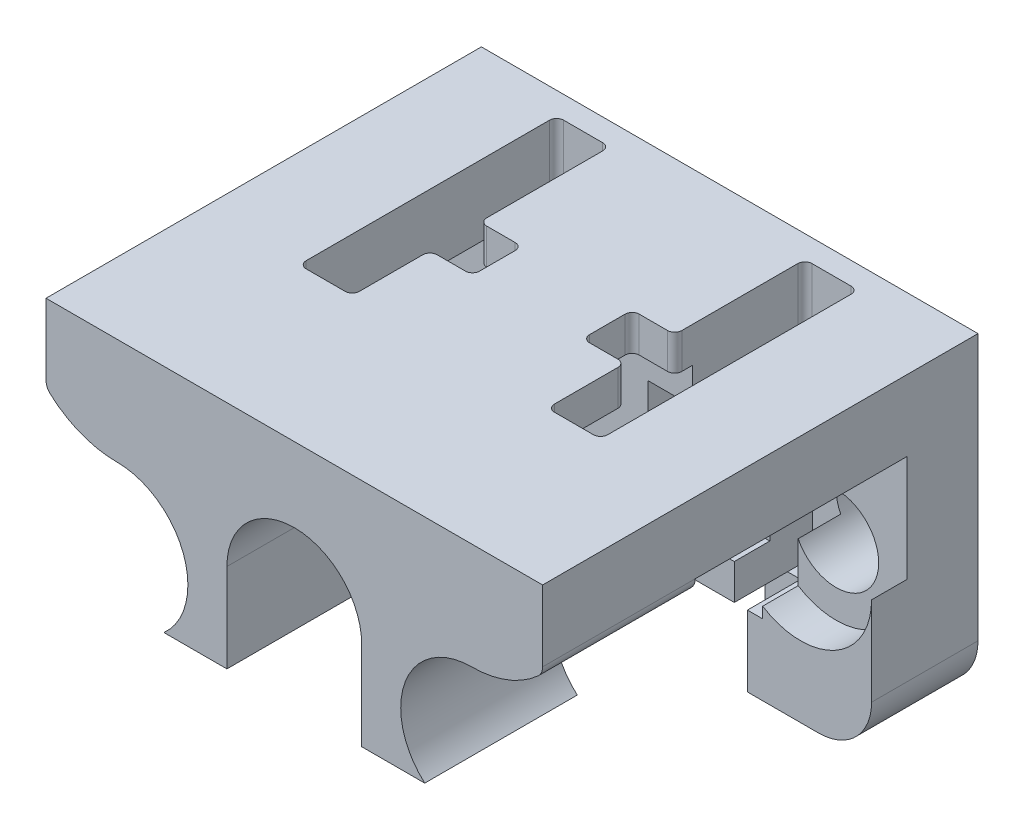
SolidWorks part; units mm, degrees
ref_plane "Front Plane" through (0, 0, 0) normal (0, 0, 1) x (1, 0, 0)
ref_plane "Top Plane" through (0, 0, 0) normal (0, 1, 0) x (1, 0, 0)
ref_plane "Right Plane" through (0, 0, 0) normal (1, 0, 0) x (0, 0, -1)
sketch "Sketch1" plane through (0, 0, 0) normal (0, 0, 1) x (1, 0, 0)
  line L1 (-7, -3.5) -> (7, -3.5)
  line L2 (-7, -3.5) -> (-7, 3.5)
  line L3 (-7, 3.5) -> (7, 3.5)
  line L4 (7, -3.5) -> (7, 3.5)
  line L5 (-7, -3.5) -> (7, 3.5) construction
  line L6 (-7, 3.5) -> (7, -3.5) construction
  point P0 (0, 0)
  dimension "D1" = 14
  dimension "D2" = 7
extrude "Boss-Extrude1" add sketch "Sketch1" along normal blind 2
fillet "Fillet1" radius 1.5 2 edges at (-7, -3.5, 1) (7, -3.5, 1)
hole_wizard "M2 Clearance Hole1" positions "Sketch2" profile "Sketch3" hole size "M2" standard "ISO" end condition through all
sketch "Sketch2" plane through (0, 0, 2) normal (0, 0, 1) x (1, 0, 0)
  line L0 (7, 3.5) -> (-7, 3.5) construction
  line L1 (0, 0) -> (0, 2.7622) construction
  point P0 (-5, 0.5)
  point P2 (5, 0.5)
  dimension "D1" = 3
  dimension "D2" = 10
sketch "Sketch3" plane through (-5, 0.5, 2) normal (1, 0, 0) x (0, -1, 0)
  line L0 (0, 0) -> (0, 2)
  line L1 (0, 2) -> (1.2, 2)
  line L2 (1.2, 2) -> (1.2, 0)
  line L5 (1.2, 0) -> (0, 0)
  line L11 (0, -6.35) -> (0, 107.95) construction
  dimension "Thru Hole Dia." = 2.4
  dimension "Thru Hole Depth" = 2
sketch "Sketch4" plane through (0, 3.5, 0) normal (0, 1, 0) x (1, 0, 0)
  line L0 (7, 0) -> (-7, 0) construction
  line L1 (-7, 0) -> (7, 0)
  line L2 (-7, 0) -> (-7, -12.2738)
  line L3 (-7, -12.2738) -> (7, -12.2738)
  line L4 (7, 0) -> (7, -12.2738)
extrude "Boss-Extrude2" add sketch "Sketch4" along normal blind 2
sketch "Sketch5" plane through (0, 0, 2) normal (0, 0, 1) x (1, 0, 0)
  line L0 (-5.5, -3.5) -> (5.5, -3.5) construction
  line L1 (-5.5, -3.5) -> (5.5, -3.5)
  line L2 (7, -2) -> (7, 3.5) construction
  line L3 (-7, 3.5) -> (-7, -2) construction
  line L4 (7, -2) -> (7, 3.5)
  line L5 (-7, 3.5) -> (-7, -2)
  line L6 (-3.2679, -0.5) -> (3.2679, -0.5)
  arc A0 (5.5, -3.5) -> (7, -2) centre (5.5, -2) ccw construction
  arc A1 (-7, -2) -> (-5.5, -3.5) centre (-5.5, -2) ccw construction
  arc A2 (5.5, -3.5) -> (7, -2) centre (5.5, -2) ccw
  arc A3 (-7, -2) -> (-5.5, -3.5) centre (-5.5, -2) ccw
  circle A4 centre (-5, 0.5) radius 2
  circle A5 centre (5, 0.5) radius 2
  arc M7 (-7, -2) -> (-5.5, -3.5) centre (-5.5, -2) ccw
  line M8 (-5.5, -3.5) -> (5.5, -3.5)
  arc M9 (5.5, -3.5) -> (7, -2) centre (5.5, -2) ccw
  line M10 (7, -2) -> (7, 3.5)
  dimension "D1" = 3
extrude "Boss-Extrude3" add sketch "Sketch5" along normal blind 1 contours A5 L6 A4 L5 M7 M8 M9 M10
sketch "Sketch6" plane through (0, 0, 0) normal (0, 0, -1) x (-1, 0, 0)
  line L0 (5.5, -3.5) -> (-5.5, -3.5) construction
  line L1 (-2.5, -3.5) -> (2.5, -3.5)
  line L2 (-2.5, -3.5) -> (-2.5, 0)
  line L3 (-2.5, 0) -> (2.5, 0)
  line L4 (2.5, -3.5) -> (2.5, 0)
  line L5 (5.5, -3.5) -> (-5.5, -3.5) construction
  point P11 (0, -3.5)
  dimension "D1" = 5
  dimension "D2" = 3.5
extrude "Cut-Extrude1" cut sketch "Sketch6" against normal blind 1.5
sketch "Sketch7" plane through (0, 0, 1.5) normal (0, 0, -1) x (-1, 0, 0)
  line L1 (-3.5, -3.5) -> (3.5, -3.5)
  line L2 (-3.5, -3.5) -> (-3.5, -1.5)
  line L3 (-3.5, -1.5) -> (3.5, -1.5)
  line L4 (3.5, -3.5) -> (3.5, -1.5)
  line L5 (-2.5, -3.5) -> (-5.5, -3.5) construction
  point P5 (0, -3.5)
  dimension "D1" = 2
  dimension "D2" = 7
extrude "Cut-Extrude2" cut sketch "Sketch7" against normal up to next
sketch "Sketch8" plane through (0, 0, 2) normal (0, 0, 1) x (1, 0, 0)
  line L1 (-1.5, -1.5) -> (1.5, -1.5)
  line L2 (-1.5, -1.5) -> (-1.5, 3.5)
  line L3 (-1.5, 3.5) -> (1.5, 3.5)
  line L4 (1.5, -1.5) -> (1.5, 3.5)
  line L5 (7, 3.5) -> (-7, 3.5) construction
  line L6 (-3.5, -1.5) -> (3.5, -1.5) construction
  circle A0 centre (-5, 0.5) radius 2
  circle A1 centre (5, 0.5) radius 2
  arc A2 (3.2679, -0.5) -> (7, 0.5) centre (5, 0.5) ccw construction
  point P17 (0, -1.5)
  line M8 (-3.2679, -0.5) -> (3.2679, -0.5)
  line M12 (7, 3.5) -> (-7, 3.5)
  dimension "D1" = 3
extrude "Boss-Extrude4" add sketch "Sketch8" along normal blind 1.8 contours L4 L2 M8 M12 | L1 L4 L2 M8
sketch "Sketch9" plane through (0, 5.5, 0) normal (0, 1, 0) x (1, 0, 0)
  line L0 (7, 0) -> (-7, 0) construction
  line L1 (-2.95, -7.89) -> (-4.05, -7.89)
  line L2 (-2.75, -7.69) -> (-2.75, -5.9)
  line L3 (-2.95, -0.63) -> (-4.05, -0.63)
  line L4 (-4.25, -7.69) -> (-4.25, -0.83)
  line L5 (-7, 0) -> (-7, -12.2738) construction
  line L6 (0, 0) -> (0, -11.1853) construction
  line L11 (-2.55, -5.7) -> (-1.75, -5.7)
  line L12 (-1.55, -5.5) -> (-1.55, -4.5)
  line L13 (-1.75, -4.3) -> (-2.55, -4.3)
  line L14 (-2.75, -4.1) -> (-2.75, -0.83)
  line L15 (2.75, -4.1) -> (2.75, -0.83)
  line L16 (1.75, -4.3) -> (2.55, -4.3)
  line L17 (1.55, -5.5) -> (1.55, -4.5)
  line L18 (2.55, -5.7) -> (1.75, -5.7)
  line L19 (4.25, -7.69) -> (4.25, -0.83)
  line L20 (2.95, -0.63) -> (4.05, -0.63)
  line L21 (2.75, -7.69) -> (2.75, -5.9)
  line L22 (2.95, -7.89) -> (4.05, -7.89)
  arc A0 (-2.95, -7.89) -> (-2.75, -7.69) centre (-2.95, -7.69) ccw
  arc A1 (-2.75, -0.83) -> (-2.95, -0.63) centre (-2.95, -0.83) ccw
  arc A2 (-4.05, -0.63) -> (-4.25, -0.83) centre (-4.05, -0.83) ccw
  arc A3 (-4.05, -7.89) -> (-4.25, -7.69) centre (-4.05, -7.69) cw
  arc A8 (-2.55, -5.7) -> (-2.75, -5.9) centre (-2.55, -5.9) ccw
  arc A9 (-1.75, -5.7) -> (-1.55, -5.5) centre (-1.75, -5.5) ccw
  arc A10 (-1.55, -4.5) -> (-1.75, -4.3) centre (-1.75, -4.5) ccw
  arc A11 (-2.55, -4.3) -> (-2.75, -4.1) centre (-2.55, -4.1) cw
  arc A12 (2.55, -4.3) -> (2.75, -4.1) centre (2.55, -4.1) ccw
  arc A13 (1.55, -4.5) -> (1.75, -4.3) centre (1.75, -4.5) cw
  arc A14 (1.75, -5.7) -> (1.55, -5.5) centre (1.75, -5.5) cw
  arc A15 (2.55, -5.7) -> (2.75, -5.9) centre (2.55, -5.9) cw
  arc A16 (4.05, -7.89) -> (4.25, -7.69) centre (4.05, -7.69) ccw
  arc A17 (4.05, -0.63) -> (4.25, -0.83) centre (4.05, -0.83) cw
  arc A18 (2.75, -0.83) -> (2.95, -0.63) centre (2.95, -0.83) cw
  arc A19 (2.95, -7.89) -> (2.75, -7.69) centre (2.95, -7.69) cw
  point P12 (-2.75, -7.89)
  point P15 (-2.75, -0.63)
  point P18 (-4.25, -0.63)
  point P51 (-2.75, -4.3)
  point P61 (2.75, -4.3)
  point P62 (4.25, -0.63)
  point P63 (2.75, -0.63)
  point P64 (2.75, -7.89)
  dimension "D5" = 0.2
  dimension "D9" = 0.2
  dimension "D1" = 1.5
  dimension "D2" = 7.26
  dimension "D3" = 0.63
  dimension "D4" = 2.75
  dimension "D6" = 1.2
  dimension "D7" = 1.4
  dimension "D8" = 4.3
extrude "Cut-Extrude3" cut sketch "Sketch9" against normal up to surface (2 mm away) up to face at (0, 3.5, 5.0184)
sketch "Sketch10" plane through (0, 3.5, 0) normal (0, -1, 0) x (1, 0, 0)
  line L1 (4.05, 7.89) -> (-4.05, 7.89)
  line L2 (4.05, 7.89) -> (4.05, 3.8)
  line L3 (4.05, 3.8) -> (-4.05, 3.8)
  line L4 (-4.05, 7.89) -> (-4.05, 3.8)
  line L5 (1.5, 3.8) -> (-1.5, 3.8) construction
extrude "Cut-Extrude4" cut sketch "Sketch10" against normal blind 1
sketch "Sketch12" plane through (0, 0, 12.2738) normal (0, 0, 1) x (1, 0, 0)
  line L0 (-7, 3.5) -> (-7, -1)
  line L1 (-7, 0.5) -> (-7, -2) construction
  line L2 (-7, -1) -> (-1.9, -1)
  line L3 (-1.9, -1) -> (-1.9, 1.5)
  line L4 (1.9, 1.5) -> (1.9, -1)
  line L5 (1.9, -1) -> (7, -1)
  line L6 (7, -2) -> (7, 0.5) construction
  line L7 (7, -1) -> (7, 3.5)
  line L8 (7, 3.5) -> (-7, 3.5)
  line L9 (0, 0) -> (0, 6.7843) construction
  line L12 (7, 5.5) -> (7, 3.5) construction
  arc A0 (-1.9, 1.5) -> (1.9, 1.5) centre (0, 1.5) cw
  circle A1 centre (5, 0.5) radius 2
  arc A2 (6.8737, 3.2171) -> (7, 3.5) centre (6.62, 3.5) ccw
  arc A3 (6.8737, 3.2171) -> (5, 2.5) centre (5, 5.3065) cw
  circle A4 centre (-5, 0.5) radius 2
  arc A5 (-6.8737, 3.2171) -> (-5, 2.5) centre (-5, 5.3065) ccw
  arc A6 (-6.8737, 3.2171) -> (-7, 3.5) centre (-6.62, 3.5) cw
  line M9 (-7, 3.5) -> (7, 3.5)
  dimension "D1" = 1.9
  dimension "D4" = 4
  dimension "D5" = 0.38
  dimension "D2" = 2
  dimension "D3" = 4.5
extrude "Boss-Extrude5" add sketch "Sketch12" against normal blind 4.3 contours L8 A0 L4 L5 L7 | L3 A0 L0 L2 M9
sketch "Sketch13" plane through (0, 3.5, 0) normal (0, 1, 0) x (1, 0, 0)
  line L0 (3.2679, -3) -> (7, -3) construction
  line L1 (3.93, -3) -> (3.13, -3)
  line L2 (3.93, -3) -> (3.93, -0.8)
  line L3 (3.93, -0.8) -> (3.13, -0.8)
  line L4 (3.13, -3) -> (3.13, -0.8)
  line L6 (4.25, -7.69) -> (4.25, -0.83) construction
  point P7 (3.53, -0.8)
  dimension "D1" = 0.8
  dimension "D2" = 2.2
  dimension "D3" = 0.72
extrude "Cut-Extrude5" cut sketch "Sketch13" against normal blind 5
mirror "Mirror1" about plane through (0, 0, 0) normal (1, 0, 0) of "Cut-Extrude5"
